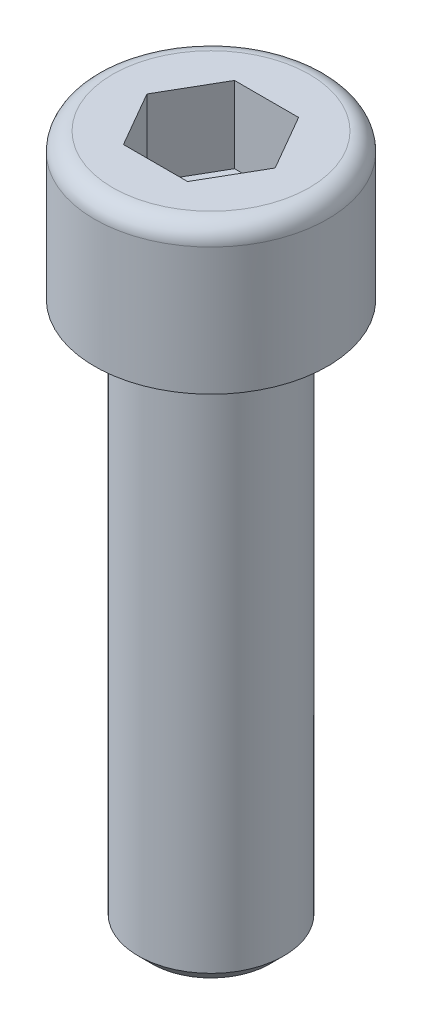
SolidWorks part; units mm, degrees
material "Acier non allié"
ref_plane "Plan de face" through (0, 0, 0) normal (0, 0, 1) x (1, 0, 0)
ref_plane "Plan de dessus" through (0, 0, 0) normal (0, 1, 0) x (1, 0, 0)
ref_plane "Plan de droite" through (0, 0, 0) normal (1, 0, 0) x (0, 0, -1)
sketch "Esquisse1" plane through (0, 0, 0) normal (0, 0, 1) x (1, 0, 0)
  line L0 (6.4, 8) -> (0, 8)
  line L1 (0, 8) -> (0, 0)
  line L2 (0, 0) -> (6.4, 0)
  line L3 (6.4, 0) -> (6.4, 8)
  line L4 (0, 8) -> (0, 0) construction
revolve "Révolution1" add sketch "Esquisse1" angle 360 about L4
sketch "Esquisse2" plane through (0, 0, 0) normal (0, -1, 0) x (1, 0, 0)
  circle A0 centre (0, 0) radius 4
extrude "Boss.-Extru.1" add sketch "Esquisse2" along normal blind 30
sketch "Esquisse3" plane through (0, 8, 0) normal (0, 1, 0) x (-1, 0, 0)
  line L0 (1.7609, 3.05) -> (-1.7609, 3.05)
  line L1 (-1.7609, 3.05) -> (-3.5218, 0)
  line L2 (-3.5218, 0) -> (-1.7609, -3.05)
  line L3 (-1.7609, -3.05) -> (1.7609, -3.05)
  line L4 (1.7609, -3.05) -> (3.5218, 0)
  line L5 (3.5218, 0) -> (1.7609, 3.05)
extrude "Enlèv. mat.-Extru.1" cut sketch "Esquisse3" against normal blind 4.2
chamfer "Chanfrein1" distance 0.75 angle 45 1 edges at (0, -30, -4)
fillet "Congé1" radius 1 1 edges at (0, 8, -6.4)
